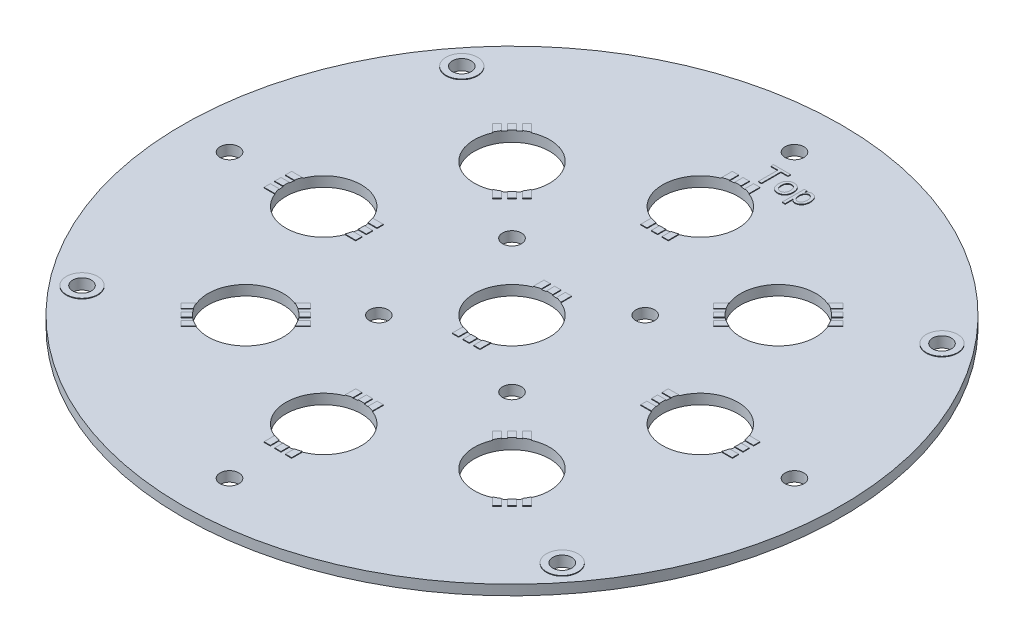
SolidWorks part; units mm, degrees
material "A-Glass Fiber"
ref_plane "Front Plane" through (0, 0, 0) normal (0, 0, 1) x (1, 0, 0)
ref_plane "Top Plane" through (0, 0, 0) normal (0, 1, 0) x (1, 0, 0)
ref_plane "Right Plane" through (0, 0, 0) normal (1, 0, 0) x (0, 0, -1)
sketch "Lenses Heatsink Dimensions Base Sketch1" plane through (0, 0, 0) normal (0, 1, 0) x (1, 0, 0)
  line L0 (-1.7436, 3.6) -> (1.7436, 3.6) construction
  line L1 (-1.7436, -3.6) -> (1.7436, -3.6) construction
  line L2 (0, 0) -> (0, 3.6) construction
  line L3 (0, 0) -> (0, -3.6) construction
  line L4 (-2.2, 0) -> (-2.2, 7.3) construction
  line L5 (0, 0) -> (2.2, 0) construction
  line L6 (0, 0) -> (0, 7.3) construction
  line L7 (0, 7.3) -> (2.2, 7.3) construction
  line L8 (2.2, 0) -> (2.2, 7.3) construction
  line L9 (0, 0) -> (-2.2, 0) construction
  line L10 (0, 0) -> (0, -7.3) construction
  line L11 (0, -7.3) -> (-2.2, -7.3) construction
  line L12 (-2.2, 0) -> (-2.2, -7.3) construction
  line L13 (-2.2, 7.3) -> (0, 7.3) construction
  line L14 (0, -7.3) -> (2.2, -7.3) construction
  line L15 (2.2, -7.3) -> (2.2, 0) construction
  line L16 (0, 0) -> (33.5, 0) construction
  line L17 (-33.5, 33.5) -> (33.5, 33.5) construction
  line L18 (-33.5, 33.5) -> (-33.5, -33.5) construction
  line L19 (-33.5, -33.5) -> (33.5, -33.5) construction
  line L20 (33.5, 33.5) -> (33.5, -33.5) construction
  line L21 (0, 0) -> (-33.5, 0) construction
  line L22 (0, 0) -> (0, -33.5) construction
  line L23 (0, 0) -> (0, 33.5) construction
  line L24 (24.8194, 27.9307) -> (19.6576, 22.7688) construction
  line L25 (2.2, 37.3) -> (-2.2, 37.3) construction
  line L26 (2.2, 37.3) -> (2.2, 30) construction
  line L27 (2.2, 30) -> (-2.2, 30) construction
  line L28 (-2.2, 37.3) -> (-2.2, 30) construction
  line L29 (-2.2, 22.7) -> (2.2, 22.7) construction
  line L30 (-2.2, 22.7) -> (-2.2, 30) construction
  line L31 (27.9307, 24.8194) -> (24.8194, 27.9307) construction
  line L32 (2.2, 22.7) -> (2.2, 30) construction
  line L33 (27.9307, 24.8194) -> (22.7688, 19.6576) construction
  line L34 (14.4957, 17.607) -> (19.6576, 22.7688) construction
  line L35 (14.4957, 17.607) -> (17.607, 14.4957) construction
  line L36 (17.607, 14.4957) -> (22.7688, 19.6576) construction
  line L37 (37.3, 2.2) -> (30, 2.2) construction
  line L38 (37.3, -2.2) -> (37.3, 2.2) construction
  line L39 (37.3, -2.2) -> (30, -2.2) construction
  line L40 (22.7, 2.2) -> (30, 2.2) construction
  line L41 (22.7, 2.2) -> (22.7, -2.2) construction
  line L42 (22.7, -2.2) -> (30, -2.2) construction
  line L43 (27.9307, -24.8194) -> (22.7688, -19.6576) construction
  line L44 (24.8194, -27.9307) -> (27.9307, -24.8194) construction
  line L45 (24.8194, -27.9307) -> (19.6576, -22.7688) construction
  line L46 (17.607, -14.4957) -> (22.7688, -19.6576) construction
  line L47 (17.607, -14.4957) -> (14.4957, -17.607) construction
  line L48 (14.4957, -17.607) -> (19.6576, -22.7688) construction
  line L49 (2.2, -37.3) -> (2.2, -30) construction
  line L50 (-2.2, -37.3) -> (2.2, -37.3) construction
  line L51 (-2.2, -37.3) -> (-2.2, -30) construction
  line L52 (2.2, -22.7) -> (2.2, -30) construction
  line L53 (2.2, -22.7) -> (-2.2, -22.7) construction
  line L54 (-2.2, -22.7) -> (-2.2, -30) construction
  line L55 (-24.8194, -27.9307) -> (-19.6576, -22.7688) construction
  line L56 (-27.9307, -24.8194) -> (-24.8194, -27.9307) construction
  line L57 (-27.9307, -24.8194) -> (-22.7688, -19.6576) construction
  line L58 (-14.4957, -17.607) -> (-19.6576, -22.7688) construction
  line L59 (-14.4957, -17.607) -> (-17.607, -14.4957) construction
  line L60 (-17.607, -14.4957) -> (-22.7688, -19.6576) construction
  line L61 (-37.3, -2.2) -> (-30, -2.2) construction
  line L62 (-37.3, 2.2) -> (-37.3, -2.2) construction
  line L63 (-37.3, 2.2) -> (-30, 2.2) construction
  line L64 (-22.7, -2.2) -> (-30, -2.2) construction
  line L65 (-22.7, -2.2) -> (-22.7, 2.2) construction
  line L66 (-22.7, 2.2) -> (-30, 2.2) construction
  line L67 (-27.9307, 24.8194) -> (-22.7688, 19.6576) construction
  line L68 (-24.8194, 27.9307) -> (-27.9307, 24.8194) construction
  line L69 (-24.8194, 27.9307) -> (-19.6576, 22.7688) construction
  line L70 (-17.607, 14.4957) -> (-22.7688, 19.6576) construction
  line L71 (-17.607, 14.4957) -> (-14.4957, 17.607) construction
  line L72 (-14.4957, 17.607) -> (-19.6576, 22.7688) construction
  line L73 (38.25, 30.25) -> (38.25, 33.5) construction
  line L74 (33.5, 33.5) -> (41.5, 33.5) construction
  line L75 (-33.5, 33.5) -> (-41.5, 33.5) construction
  line L76 (33.5, -33.5) -> (41.5, -33.5) construction
  line L77 (41.5, 33.5) -> (41.5, -33.5) construction
  line L78 (38.25, 30.25) -> (41.5, 30.25) construction
  line L79 (-33.5, -33.5) -> (-41.5, -33.5) construction
  line L80 (-41.5, 33.5) -> (-41.5, -33.5) construction
  circle A0 centre (0, 30) radius 2.7 construction
  circle A1 centre (0, 0) radius 2.7 construction
  circle A2 centre (0, 0) radius 4 construction
  circle A3 centre (0, 0) radius 30 construction
  circle A4 centre (0, 30) radius 4 construction
  circle A5 centre (0, 0) radius 10.5 construction
  circle A6 centre (0, 30) radius 10.5 construction
  circle A7 centre (21.2132, 21.2132) radius 10.5 construction
  circle A8 centre (21.2132, 21.2132) radius 4 construction
  circle A9 centre (21.2132, 21.2132) radius 2.7 construction
  circle A10 centre (30, 0) radius 10.5 construction
  circle A11 centre (30, 0) radius 4 construction
  circle A12 centre (30, 0) radius 2.7 construction
  circle A13 centre (21.2132, -21.2132) radius 10.5 construction
  circle A14 centre (21.2132, -21.2132) radius 4 construction
  circle A15 centre (21.2132, -21.2132) radius 2.7 construction
  circle A16 centre (0, -30) radius 10.5 construction
  circle A17 centre (0, -30) radius 4 construction
  circle A18 centre (0, -30) radius 2.7 construction
  circle A19 centre (-21.2132, -21.2132) radius 10.5 construction
  circle A20 centre (-21.2132, -21.2132) radius 4 construction
  circle A21 centre (-21.2132, -21.2132) radius 2.7 construction
  circle A22 centre (-30, 0) radius 10.5 construction
  circle A23 centre (-30, 0) radius 4 construction
  circle A24 centre (-30, 0) radius 2.7 construction
  circle A25 centre (-21.2132, 21.2132) radius 10.5 construction
  circle A26 centre (-21.2132, 21.2132) radius 4 construction
  circle A27 centre (-21.2132, 21.2132) radius 2.7 construction
  circle A28 centre (38.25, 30.25) radius 1.5 construction
  circle A29 centre (-38.25, 30.25) radius 1.5 construction
  circle A30 centre (38.25, -30.25) radius 1.5 construction
  circle A31 centre (-38.25, -30.25) radius 1.5 construction
  point P110 (0, 0)
  dimension "D1" = 67
  dimension "D2" = 5.4
  dimension "D3" = 8
  dimension "D8" = 21
  dimension "D10" = 65.4
  dimension "D12" = 81
  dimension "D14" = 3
  dimension "D4" = 7.2
  dimension "D5" = 4.4
  dimension "D6" = 14.6
  dimension "D7" = 30
  dimension "D11" = 60
  dimension "D13" = 83
  dimension "D15" = 3.25
  dimension "D16" = 76.5
  dimension "D17" = 60.5
  dimension "D18" = 3.25
  dimension "D9" = 8
sketch "Sketch2" plane through (0, 0, 0) normal (0, 1, 0) x (1, 0, 0)
  line L0 (0, 0) -> (-33.5, 0) construction
  line L1 (0, 0) -> (0, 45) construction
  line L2 (-7.4246, 7.4246) -> (-10.6066, 10.6066) construction
  line L3 (-10.6066, 10.6066) -> (-13.7886, 13.7886) construction
  line L4 (-7.4246, 7.4246) -> (0, 0) construction
  circle A0 centre (0, 0) radius 52.5
  circle A1 centre (-38.25, 30.25) radius 1.5
  circle A2 centre (38.25, 30.25) radius 1.5
  circle A3 centre (38.25, -30.25) radius 1.5
  circle A4 centre (-38.25, -30.25) radius 1.5
  circle A5 centre (0, 0) radius 10.5 construction
  circle A6 centre (-21.2132, 21.2132) radius 10.5 construction
  circle A7 centre (-38.25, 30.25) radius 1.5 construction
  circle A19 centre (0, 45) radius 1.5
  circle A20 centre (45, 0) radius 1.5
  circle A21 centre (0, -45) radius 1.5
  circle A22 centre (-45, 0) radius 1.5
  circle A23 centre (-10.6066, 10.6066) radius 1.5
  circle A24 centre (10.6066, 10.6066) radius 1.5
  circle A25 centre (10.6066, -10.6066) radius 1.5
  circle A26 centre (-10.6066, -10.6066) radius 1.5
  point P41 (0, 0)
  point P51 (0, 0)
  point P67 (0, 0)
  dimension "D1" = 105
  dimension "D2" = 3.734
  dimension "D5" = 45
  dimension "D6" = 45
  dimension "D8" = 15
  dimension "D7" = 4
extrude "PCB 1.6mm Boss-Extrude1" add sketch "Sketch2" along normal blind 1.6
sketch "Sketch3" plane through (0, 1.6, 0) normal (0, 1, 0) x (1, 0, 0)
  line L0 (-1.2, 37.3) -> (-1.2, 22.7)
  line L1 (-2.2, 37.3) -> (-1.2, 37.3)
  line L2 (-2.2, 37.3) -> (-2.2, 22.7)
  line L3 (-2.2, 22.7) -> (-1.2, 22.7)
  line L4 (2.2, 37.3) -> (2.2, 22.7)
  line L5 (-2.2, 7.3) -> (-1.2, 7.3)
  line L6 (-2.2, 7.3) -> (-2.2, -7.3)
  line L7 (-2.2, -7.3) -> (-1.2, -7.3)
  line L8 (2.2, 7.3) -> (2.2, -7.3)
  line L9 (-0.5, 37.3) -> (-0.5, 22.7)
  line L10 (0.5, 37.3) -> (0.5, 22.7)
  line L11 (1.2, 37.3) -> (1.2, 22.7)
  line L12 (-0.5, 22.7) -> (0.5, 22.7)
  line L13 (1.2, 22.7) -> (2.2, 22.7)
  line L14 (-0.5, 37.3) -> (0.5, 37.3)
  line L15 (1.2, 37.3) -> (2.2, 37.3)
  line L16 (-1.2, 7.3) -> (-1.2, -7.3)
  line L17 (-0.5, 7.3) -> (-0.5, -7.3)
  line L18 (0.5, 7.3) -> (0.5, -7.3)
  line L19 (1.2, 7.3) -> (1.2, -7.3)
  line L20 (-0.5, -7.3) -> (0.5, -7.3)
  line L21 (1.2, -7.3) -> (2.2, -7.3)
  line L22 (-0.5, 7.3) -> (0.5, 7.3)
  line L23 (1.2, 7.3) -> (2.2, 7.3)
  line L24 (-1.2, -7.3) -> (-0.5, -7.3) construction
  line L25 (0.5, -7.3) -> (1.2, -7.3) construction
  line L26 (-1.2, 7.3) -> (-0.5, 7.3) construction
  line L27 (0.5, 7.3) -> (1.2, 7.3) construction
  line L28 (24.8194, 27.9307) -> (14.4957, 17.607)
  line L29 (14.4957, 17.607) -> (15.2028, 16.8999)
  line L30 (25.5266, 27.2236) -> (15.2028, 16.8999)
  line L31 (24.8194, 27.9307) -> (25.5266, 27.2236)
  line L32 (26.0215, 26.7286) -> (15.6978, 16.4049)
  line L33 (15.6978, 16.4049) -> (16.4049, 15.6978)
  line L34 (26.7286, 26.0215) -> (16.4049, 15.6978)
  line L35 (26.0215, 26.7286) -> (26.7286, 26.0215)
  line L36 (27.2236, 25.5266) -> (16.8999, 15.2028)
  line L37 (16.8999, 15.2028) -> (17.607, 14.4957)
  line L38 (27.9307, 24.8194) -> (17.607, 14.4957)
  line L39 (27.2236, 25.5266) -> (27.9307, 24.8194)
  line L40 (37.3, 2.2) -> (22.7, 2.2)
  line L41 (22.7, 2.2) -> (22.7, 1.2)
  line L42 (37.3, 1.2) -> (22.7, 1.2)
  line L43 (37.3, 2.2) -> (37.3, 1.2)
  line L44 (37.3, 0.5) -> (22.7, 0.5)
  line L45 (22.7, 0.5) -> (22.7, -0.5)
  line L46 (37.3, -0.5) -> (22.7, -0.5)
  line L47 (37.3, 0.5) -> (37.3, -0.5)
  line L48 (37.3, -1.2) -> (22.7, -1.2)
  line L49 (22.7, -1.2) -> (22.7, -2.2)
  line L50 (37.3, -2.2) -> (22.7, -2.2)
  line L51 (37.3, -1.2) -> (37.3, -2.2)
  line L52 (27.9307, -24.8194) -> (17.607, -14.4957)
  line L53 (17.607, -14.4957) -> (16.8999, -15.2028)
  line L54 (27.2236, -25.5266) -> (16.8999, -15.2028)
  line L55 (27.9307, -24.8194) -> (27.2236, -25.5266)
  line L56 (26.7286, -26.0215) -> (16.4049, -15.6978)
  line L57 (16.4049, -15.6978) -> (15.6978, -16.4049)
  line L58 (26.0215, -26.7286) -> (15.6978, -16.4049)
  line L59 (26.7286, -26.0215) -> (26.0215, -26.7286)
  line L60 (25.5266, -27.2236) -> (15.2028, -16.8999)
  line L61 (15.2028, -16.8999) -> (14.4957, -17.607)
  line L62 (24.8194, -27.9307) -> (14.4957, -17.607)
  line L63 (25.5266, -27.2236) -> (24.8194, -27.9307)
  line L64 (2.2, -37.3) -> (2.2, -22.7)
  line L65 (2.2, -22.7) -> (1.2, -22.7)
  line L66 (1.2, -37.3) -> (1.2, -22.7)
  line L67 (2.2, -37.3) -> (1.2, -37.3)
  line L68 (0.5, -37.3) -> (0.5, -22.7)
  line L69 (0.5, -22.7) -> (-0.5, -22.7)
  line L70 (-0.5, -37.3) -> (-0.5, -22.7)
  line L71 (0.5, -37.3) -> (-0.5, -37.3)
  line L72 (-1.2, -37.3) -> (-1.2, -22.7)
  line L73 (-1.2, -22.7) -> (-2.2, -22.7)
  line L74 (-2.2, -37.3) -> (-2.2, -22.7)
  line L75 (-1.2, -37.3) -> (-2.2, -37.3)
  line L76 (-24.8194, -27.9307) -> (-14.4957, -17.607)
  line L77 (-14.4957, -17.607) -> (-15.2028, -16.8999)
  line L78 (-25.5266, -27.2236) -> (-15.2028, -16.8999)
  line L79 (-24.8194, -27.9307) -> (-25.5266, -27.2236)
  line L80 (-26.0215, -26.7286) -> (-15.6978, -16.4049)
  line L81 (-15.6978, -16.4049) -> (-16.4049, -15.6978)
  line L82 (-26.7286, -26.0215) -> (-16.4049, -15.6978)
  line L83 (-26.0215, -26.7286) -> (-26.7286, -26.0215)
  line L84 (-27.2236, -25.5266) -> (-16.8999, -15.2028)
  line L85 (-16.8999, -15.2028) -> (-17.607, -14.4957)
  line L86 (-27.9307, -24.8194) -> (-17.607, -14.4957)
  line L87 (-27.2236, -25.5266) -> (-27.9307, -24.8194)
  line L88 (-37.3, -2.2) -> (-22.7, -2.2)
  line L89 (-22.7, -2.2) -> (-22.7, -1.2)
  line L90 (-37.3, -1.2) -> (-22.7, -1.2)
  line L91 (-37.3, -2.2) -> (-37.3, -1.2)
  line L92 (-37.3, -0.5) -> (-22.7, -0.5)
  line L93 (-22.7, -0.5) -> (-22.7, 0.5)
  line L94 (-37.3, 0.5) -> (-22.7, 0.5)
  line L95 (-37.3, -0.5) -> (-37.3, 0.5)
  line L96 (-37.3, 1.2) -> (-22.7, 1.2)
  line L97 (-22.7, 1.2) -> (-22.7, 2.2)
  line L98 (-37.3, 2.2) -> (-22.7, 2.2)
  line L99 (-37.3, 1.2) -> (-37.3, 2.2)
  line L100 (-27.9307, 24.8194) -> (-17.607, 14.4957)
  line L101 (-17.607, 14.4957) -> (-16.8999, 15.2028)
  line L102 (-27.2236, 25.5266) -> (-16.8999, 15.2028)
  line L103 (-27.9307, 24.8194) -> (-27.2236, 25.5266)
  line L104 (-26.7286, 26.0215) -> (-16.4049, 15.6978)
  line L105 (-16.4049, 15.6978) -> (-15.6978, 16.4049)
  line L106 (-26.0215, 26.7286) -> (-15.6978, 16.4049)
  line L107 (-26.7286, 26.0215) -> (-26.0215, 26.7286)
  line L108 (-25.5266, 27.2236) -> (-15.2028, 16.8999)
  line L109 (-15.2028, 16.8999) -> (-14.4957, 17.607)
  line L110 (-24.8194, 27.9307) -> (-14.4957, 17.607)
  line L111 (-25.5266, 27.2236) -> (-24.8194, 27.9307)
  point P42 (0, 0)
  point P117 (0, 0)
  dimension "D1" = 1
  dimension "D2" = 0.7
sketch "Sketch4" plane through (0, 0, 0) normal (0, 1, 0) x (1, 0, 0)
  circle A0 centre (0, 0) radius 30 construction
  circle A1 centre (0, 0) radius 30 construction
  circle A2 centre (0, 0) radius 6
  circle A3 centre (0, 30) radius 6
  circle A4 centre (21.2132, 21.2132) radius 6
  circle A5 centre (30, 0) radius 6
  circle A6 centre (21.2132, -21.2132) radius 6
  circle A7 centre (0, -30) radius 6
  circle A8 centre (-21.2132, -21.2132) radius 6
  circle A9 centre (-30, 0) radius 6
  circle A10 centre (-21.2132, 21.2132) radius 6
  point P25 (0, 0)
  dimension "D1" = 12
extrude "Pads Boss-Extrude2" add sketch "Sketch3" along normal blind 0.1
extrude "LED Holes Cut-Extrude2" cut sketch "Sketch4" along normal up to surface (1.7 mm away) up to face at (-22.4153, 1.7, -20.0111)
sketch "Sketch5" plane through (0, 1.6, 0) normal (0, 1, 0) x (1, 0, 0)
  line L0 (0, 0) -> (0, 15.2623) construction
  line L1 (0, 0) -> (12.9783, 0) construction
  circle A0 centre (-38.25, 30.25) radius 2.5
  circle A1 centre (-38.25, 30.25) radius 1.5
  circle A2 centre (-38.25, 30.25) radius 1.5 construction
  circle A3 centre (38.25, 30.25) radius 1.5
  circle A4 centre (38.25, 30.25) radius 2.5
  circle A5 centre (38.25, -30.25) radius 2.5
  circle A6 centre (38.25, -30.25) radius 1.5
  circle A7 centre (-38.25, -30.25) radius 2.5
  circle A8 centre (-38.25, -30.25) radius 1.5
  text T0 "Top" font "Arial" height 3.5
  dimension "D1" = 5
  dimension "D2" = 38
extrude "Heatsink Holes Boss-Extrude1" add sketch "Sketch5" along normal up to surface (0.1 mm away) up to face at (-27.0272, 1.7, -24.6208)
